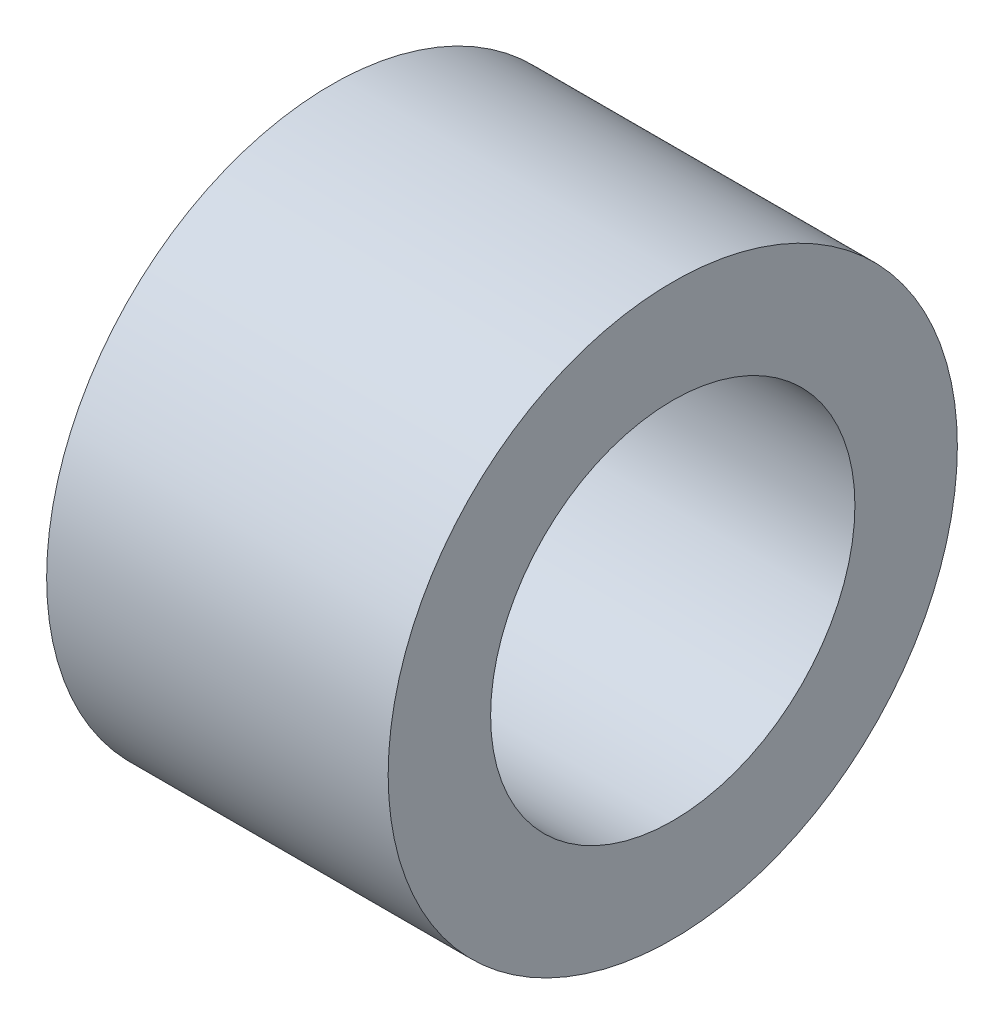
SolidWorks part; units mm, degrees
ref_plane "Front" through (0, 0, 0) normal (0, 0, 1) x (1, 0, 0)
ref_plane "Top" through (0, 0, 0) normal (0, 1, 0) x (1, 0, 0)
ref_plane "Right" through (0, 0, 0) normal (1, 0, 0) x (0, 0, -1)
sketch "Skizze1" plane through (0, 0, 0) normal (0, 0, 1) x (1, 0, 0)
  line L0 (0, 0) -> (7.877, 0) construction
  line L1 (0, 1.6) -> (3, 1.6)
  line L2 (0, 1.6) -> (0, 2.5)
  line L3 (0, 2.5) -> (3, 2.5)
  line L4 (3, 1.6) -> (3, 2.5)
  dimension "D1" = 5
  dimension "D2" = 3.2
  dimension "D3" = 3
revolve "Rotation1" add sketch "Skizze1" angle 360 about L0
